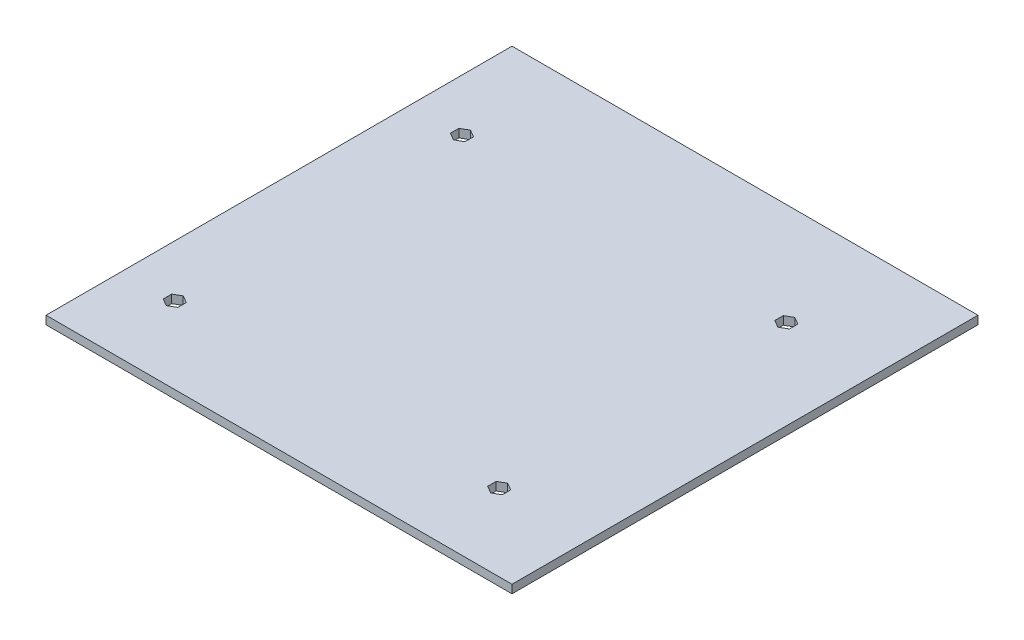
SolidWorks part; units mm, degrees
ref_plane "Front Plane" through (0, 0, 0) normal (0, 0, 1) x (1, 0, 0)
ref_plane "Top Plane" through (0, 0, 0) normal (0, 1, 0) x (1, 0, 0)
ref_plane "Right Plane" through (0, 0, 0) normal (1, 0, 0) x (0, 0, -1)
sketch "Sketch1" plane through (0, 0, 0) normal (0, 1, 0) x (1, 0, 0)
  line L1 (-75.9727, -110.777) -> (101.8273, -110.777)
  line L2 (-75.9727, -110.777) -> (-75.9727, 67.023)
  line L3 (-75.9727, 67.023) -> (101.8273, 67.023)
  line L4 (101.8273, -110.777) -> (101.8273, 67.023)
  dimension "D1" = 177.8
  dimension "D2" = 177.8
extrude "Boss-Extrude1" add sketch "Sketch1" along normal blind 3.175
sketch "Sketch2" plane through (0, 3.175, 0) normal (0, 1, 0) x (1, 0, 0)
  line L1 (-58.9335, 29.7561) -> (-58.9642, 26.53)
  line L2 (-58.9642, 26.53) -> (-56.1857, 24.8904)
  line L3 (-56.1857, 24.8904) -> (-53.3765, 26.4769)
  line L4 (-53.3765, 26.4769) -> (-53.3458, 29.703)
  line L5 (-53.3458, 29.703) -> (-56.1243, 31.3426)
  line L6 (-56.1243, 31.3426) -> (-58.9335, 29.7561)
  line L7 (67.6105, 31.3426) -> (64.8165, 29.7295)
  line L8 (64.8165, 29.7295) -> (64.8165, 26.5033)
  line L9 (64.8165, 26.5033) -> (67.6105, 24.8901)
  line L10 (67.6105, 24.8901) -> (70.4045, 26.5033)
  line L11 (70.4045, 26.5033) -> (70.4045, 29.7295)
  line L12 (70.4045, 29.7295) -> (67.6105, 31.3426)
  line L13 (-56.1857, -78.2145) -> (-58.9797, -79.8276)
  line L14 (-58.9797, -79.8276) -> (-58.9797, -83.0538)
  line L15 (-58.9797, -83.0538) -> (-56.1857, -84.667)
  line L16 (-56.1857, -84.667) -> (-53.3917, -83.0538)
  line L17 (-53.3917, -83.0538) -> (-53.3917, -79.8276)
  line L18 (-53.3917, -79.8276) -> (-56.1857, -78.2145)
  line L19 (67.6104, -78.2145) -> (64.8164, -79.8276)
  line L20 (64.8164, -79.8276) -> (64.8164, -83.0538)
  line L21 (64.8164, -83.0538) -> (67.6104, -84.667)
  line L22 (67.6104, -84.667) -> (70.4044, -83.0538)
  line L23 (70.4044, -83.0538) -> (70.4044, -79.8276)
  line L24 (70.4044, -79.8276) -> (67.6104, -78.2145)
  circle A0 centre (-56.155, 28.1165) radius 2.794 construction
  circle A1 centre (67.6105, 28.1164) radius 2.794 construction
  circle A2 centre (-56.1857, -81.4407) radius 2.794 construction
  circle A3 centre (67.6104, -81.4407) radius 2.794 construction
  point P25 (0, 0)
  point P33 (0, 0)
  point P34 (0, 0)
extrude "Cut-Extrude1" cut sketch "Sketch2" against normal blind 3.175
